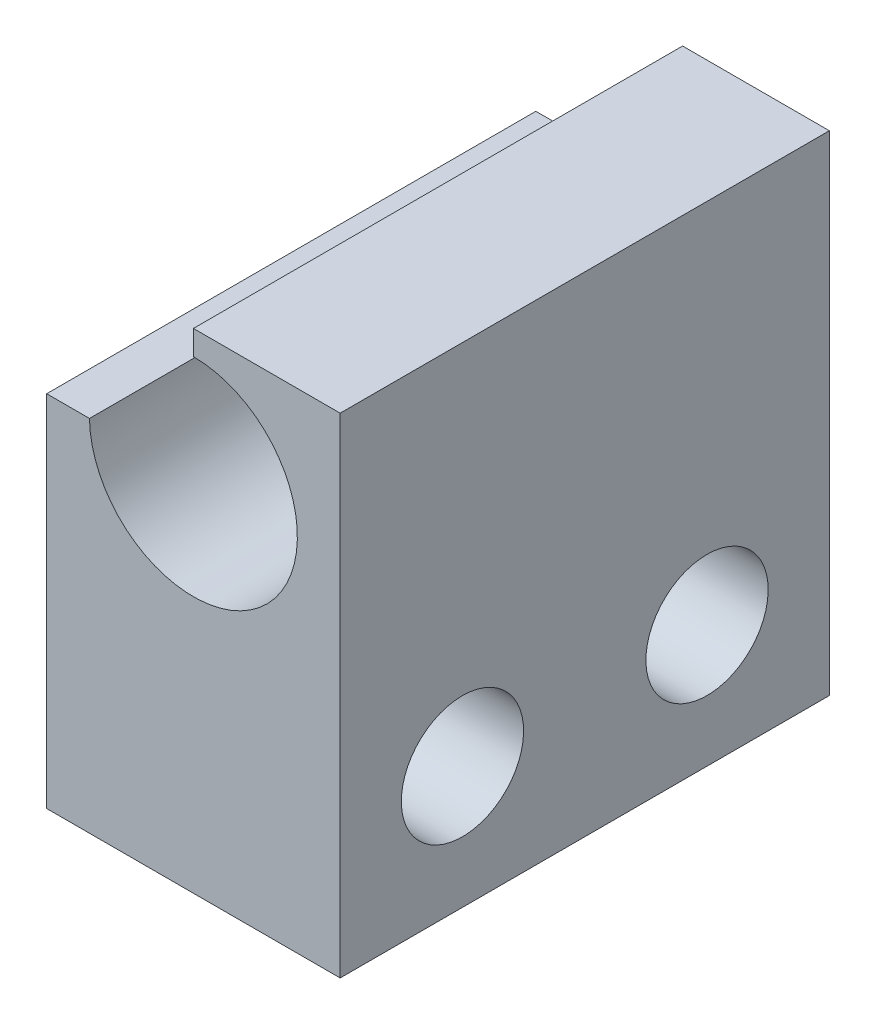
SolidWorks part; units mm, degrees
material "1060 Alloy"
ref_plane "Front Plane" through (0, 0, 0) normal (0, 0, 1) x (1, 0, 0)
ref_plane "Top Plane" through (0, 0, 0) normal (0, 1, 0) x (1, 0, 0)
ref_plane "Right Plane" through (0, 0, 0) normal (1, 0, 0) x (0, 0, -1)
sketch "Sketch1" plane through (0, 0, 0) normal (0, 0, 1) x (1, 0, 0)
  line L0 (-9.0109, 10.6477) -> (-11.234, 10.6477)
  line L1 (-11.234, 10.6477) -> (-11.234, -8.0065)
  line L2 (-11.234, -8.0065) -> (4.006, -8.0065)
  line L3 (4.006, -8.0065) -> (4.006, 17.3935)
  line L4 (4.006, 17.3935) -> (-3.614, 17.3935)
  line L5 (-3.614, 17.3935) -> (-3.614, 16.1235)
  arc A0 (-9.0109, 10.6477) -> (-3.614, 16.1235) centre (-3.614, 10.726) ccw
  dimension "D1" = 10.795
  dimension "D2" = 1.27
  dimension "D3" = 25.4
  dimension "D4" = 15.24
  dimension "D5" = 7.62
extrude "Boss-Extrude1" add sketch "Sketch1" along normal blind 25.4
sketch "Sketch2" plane through (4.006, 0, 0) normal (1, 0, 0) x (0, 0, -1)
  line L0 (-25.4, -8.0065) -> (0, -8.0065) construction
  line L2 (0, 8.382) -> (0, -8.382) construction
  line L3 (-25.4, 10.6477) -> (-25.4, -8.0065) construction
  circle A0 centre (-19.05, -1.6565) radius 3.175
  circle A1 centre (-6.35, -1.6565) radius 3.175
  dimension "D1" = 6.35
  dimension "D2" = 6.35
  dimension "D3" = 6.35
  dimension "D4" = 6.35
  dimension "D5" = 6.35
  dimension "D6" = 6.35
extrude "Cut-Extrude1" cut sketch "Sketch2" against normal blind 25.4
